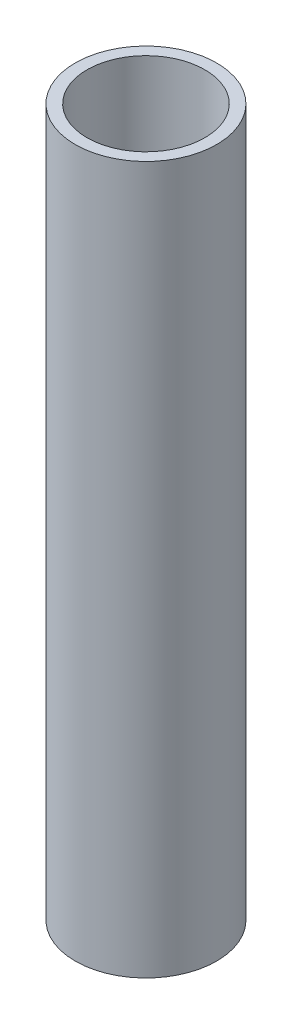
SolidWorks part; units mm, degrees
ref_plane "Front Plane" through (0, 0, 0) normal (0, 0, 1) x (1, 0, 0)
ref_plane "Top Plane" through (0, 0, 0) normal (0, 1, 0) x (1, 0, 0)
ref_plane "Right Plane" through (0, 0, 0) normal (1, 0, 0) x (0, 0, -1)
sketch "Sketch1" plane through (0, 0, 0) normal (0, 1, 0) x (1, 0, 0)
  circle A0 centre (0, 0) radius 19.05
  circle A1 centre (0, 0) radius 15.875
  dimension "D1" = 38.1
  dimension "D2" = 3.175
extrude "Boss-Extrude1" add sketch "Sketch1" along normal blind 190.5
equation "\"D2@Sketch1\"=1/8"
